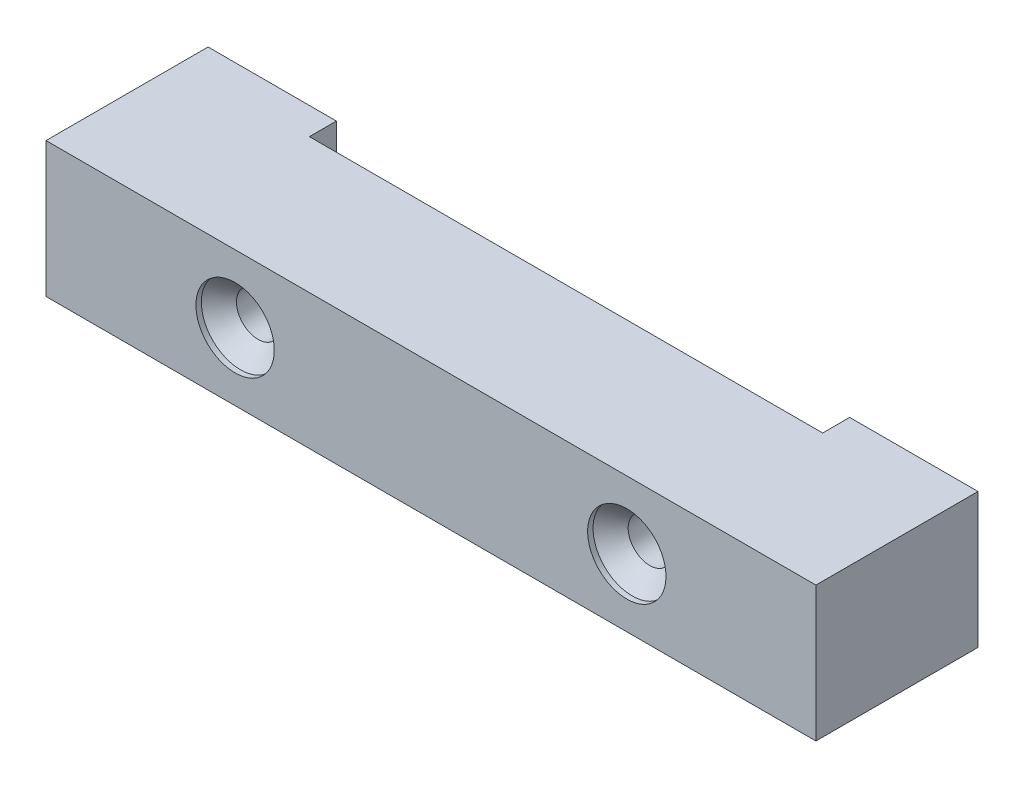
SolidWorks part; units mm, degrees
material "PET"
ref_plane "Front" through (0, 0, 0) normal (0, 0, 1) x (1, 0, 0)
ref_plane "Top" through (0, 0, 0) normal (0, 1, 0) x (1, 0, 0)
ref_plane "Right" through (0, 0, 0) normal (1, 0, 0) x (0, 0, -1)
sketch "Esquisse1" plane through (0, 0, 0) normal (0, 1, 0) x (1, 0, 0)
  line L0 (0, -12.5824) -> (0, 13.9329) construction
  line L1 (-28.5, -5) -> (28.5, -5)
  line L2 (28.5, -5) -> (28.5, 7)
  line L3 (28.5, 7) -> (19, 7)
  line L4 (19, 7) -> (19, 5)
  line L5 (19, 5) -> (-19, 5)
  line L6 (-19, 7) -> (-19, 5)
  line L7 (-28.5, 7) -> (-19, 7)
  line L8 (-28.5, -5) -> (-28.5, 7)
  point P13 (0, 5)
  point P16 (0, -5)
  dimension "D1" = 12
  dimension "D2" = 10
  dimension "D3" = 9.5
  dimension "D4" = 57
  dimension "D5" = 5
extrude "Boss.-Extru.1" add sketch "Esquisse1" along normal blind 10
sketch "Esquisse2" plane through (0, 0, -7) normal (0, 0, -1) x (-1, 0, 0)
  circle A0 centre (-23.5, 5) radius 1.55
  circle A1 centre (-23.5, 5) radius 1.55 construction
extrude "Enlèv. mat.-Extru.1" cut sketch "Esquisse2" against normal blind 7
hole_wizard "Fraisage pour vis à tête fraisée à 6 pans creux M31" positions "Esquisse3" profile "Esquisse4" countersink size "M3" standard "ISO" end condition through all
sketch "Esquisse3" plane through (0, 0, 5) normal (0, 0, 1) x (1, 0, 0)
  point P0 (14.5, 5)
sketch "Esquisse4" plane through (14.5, 5, 5) normal (1, 0, 0) x (0, -1, 0)
  line L0 (0, 0) -> (0, 12)
  line L1 (0, 12) -> (1.6, 12)
  line L2 (1.6, 12) -> (1.6, 1.7)
  line L3 (1.6, 1.7) -> (2.9, 0.4)
  line L4 (2.9, 0.4) -> (2.9, 0)
  line L6 (2.9, 0) -> (0, 0)
  line L7 (-1.6, 1.7) -> (-2.9, 0.4) construction
  line L11 (0, -6.35) -> (0, 107.95) construction
  dimension "Diamètre du perçage jusqu'au prochain" = 3.2
  dimension "Profondeur du perçage jusqu'au prochain" = 12
  dimension "Diamètre du fraisage" = 5.8
  dimension "Angle du fraisage" = 90
  dimension "Dégagement de la tête" = 0.4
mirror "Symétrie1" about plane through (0, 0, 0) normal (1, 0, 0) of "Fraisage pour vis à tête fraisée à 6 pans creux M31", "Enlèv. mat.-Extru.1"
